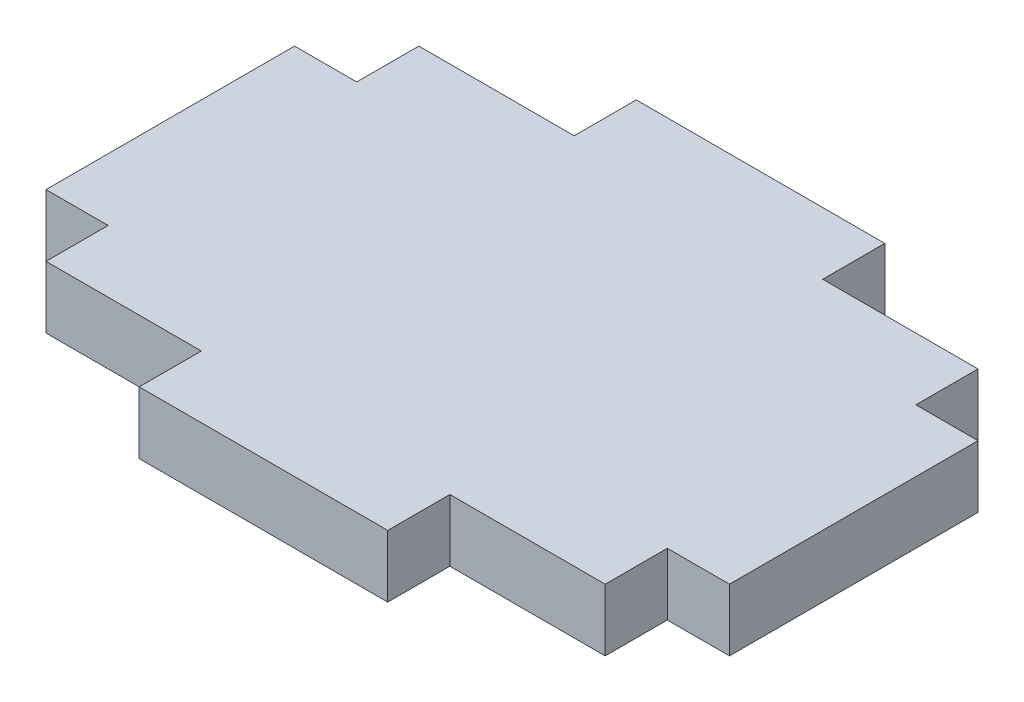
SolidWorks part; units mm, degrees
ref_plane "Front Plane" through (0, 0, 0) normal (0, 0, 1) x (1, 0, 0)
ref_plane "Top Plane" through (0, 0, 0) normal (0, 1, 0) x (1, 0, 0)
ref_plane "Right Plane" through (0, 0, 0) normal (1, 0, 0) x (0, 0, -1)
sketch "Sketch1" plane through (0, 0, 0) normal (0, 1, 0) x (1, 0, 0)
  line L1 (0, 0) -> (90, 0)
  line L2 (0, 0) -> (0, 60)
  line L3 (0, 60) -> (90, 60)
  line L4 (90, 0) -> (90, 60)
  line L5 (0, 50) -> (-10, 50)
  line L6 (0, 50) -> (0, 10)
  line L7 (0, 10) -> (-10, 10)
  line L8 (-10, 50) -> (-10, 10)
  line L9 (25, 60) -> (65, 60)
  line L10 (25, 60) -> (25, 70)
  line L11 (25, 70) -> (65, 70)
  line L12 (65, 60) -> (65, 70)
  line L13 (90, 50) -> (100, 50)
  line L14 (90, 50) -> (90, 10)
  line L15 (90, 10) -> (100, 10)
  line L16 (100, 50) -> (100, 10)
  line L17 (65, 0) -> (25, 0)
  line L18 (65, 0) -> (65, -10)
  line L19 (65, -10) -> (25, -10)
  line L20 (25, 0) -> (25, -10)
  dimension "D1" = 90
  dimension "D2" = 60
  dimension "D3" = 10
  dimension "D4" = 10
  dimension "D5" = 10
  dimension "D6" = 10
  dimension "D7" = 40
  dimension "D8" = 40
  dimension "D9" = 40
  dimension "D10" = 40
  dimension "D11" = 10
  dimension "D12" = 25
  dimension "D13" = 10
  dimension "D14" = 25
extrude "Boss-Extrude1" add sketch "Sketch1" along normal blind 10 contours L1 L4 L3 L2 | L5 L8 L7 L2 | L16 L13 L4 L15 | L1 L20 L19 L18 | L11 L12 L9 L10
